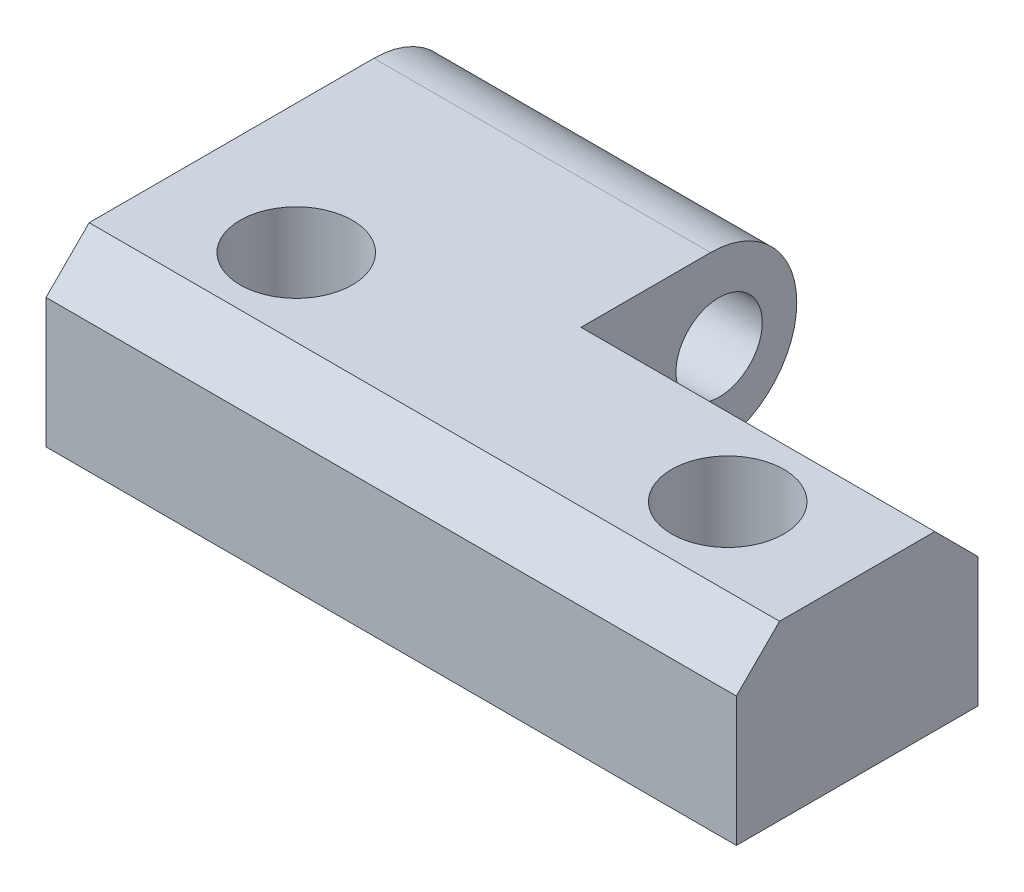
SolidWorks part; units mm, degrees
material "1.4301 (X5CrNi18-10)"
ref_plane "Vorne" through (0, 0, 0) normal (0, 0, 1) x (1, 0, 0)
ref_plane "Oben" through (0, 0, 0) normal (0, 1, 0) x (1, 0, 0)
ref_plane "Rechts" through (0, 0, 0) normal (1, 0, 0) x (0, 0, -1)
sketch "Skizze1" plane through (0, 0, 0) normal (0, 1, 0) x (1, 0, 0)
  line L0 (-40, -24) -> (40, -24)
  line L1 (40, -24) -> (40, 4)
  line L2 (40, 4) -> (-1, 4)
  line L3 (-1, 4) -> (-1, 24)
  line L4 (-1, 24) -> (-40, 24)
  line L5 (-40, 24) -> (-40, -24)
  line L6 (-40, 0) -> (0, 0) construction
  line L7 (0, -24) -> (0, 0) construction
  circle A0 centre (-25, -10) radius 6.5
  circle A1 centre (25, -10) radius 6.5
  dimension "D5" = 13
  dimension "D6" = 50
  dimension "D7" = 14
  dimension "D1" = 80
  dimension "D2" = 28
  dimension "D3" = 48
  dimension "D4" = 39
extrude "Aufsatz-Linear austragen1" add sketch "Skizze1" along normal mid plane 20
hole_wizard "Ø10.0mm Stiftloch1" positions "Skizze3" profile "Skizze2" hole size "Ø10.0" standard "Gabler-Normteile"
sketch "Skizze3" plane through (-1, 0, 0) normal (1, 0, 0) x (0, 0, -1)
  line L0 (0, 0) -> (15, 0) construction
  line L2 (24, 10) -> (24, -10) construction
  point P0 (15, 0)
  dimension "D1" = 9
sketch "Skizze2" plane through (-1, 0, -15) normal (0, 1, 0) x (0, 0, -1)
  line L0 (0, 0) -> (0, 25.0043)
  line L1 (0, 25.0043) -> (5, 22)
  line L2 (5, 22) -> (5, 0)
  line L5 (5, 0) -> (0, 0)
  line L10 (0, 25.0043) -> (-5, 22) construction
  line L11 (0, -6.35) -> (0, 107.95) construction
  dimension "Bohrerdurchmesser" = 10
  dimension "Bohrungstiefe" = 22
  dimension "Spitzenwinkel" = 118
sketch "Skizze5" plane through (-1, 0, 0) normal (1, 0, 0) x (0, 0, -1)
  line L0 (4, 10) -> (24, 10) construction
  line L1 (14, 10) -> (26, 10)
  line L2 (26, 10) -> (26, -10)
  line L3 (26, -10) -> (14, -10)
  line L4 (4, 10) -> (4, -10) construction
  line L5 (24, 10) -> (24, -10) construction
  arc A0 (14, -10) -> (14, 10) centre (14, 0) ccw
  point P10 (0, 0)
  dimension "D2" = 10
  dimension "D1" = 22
extrude "Schnitt-Linear austragen2" cut sketch "Skizze5" against normal through all
chamfer "Fase1" distance 5 angle 45 2 edges at (19.5, 10, -4) (0, 10, 24)
